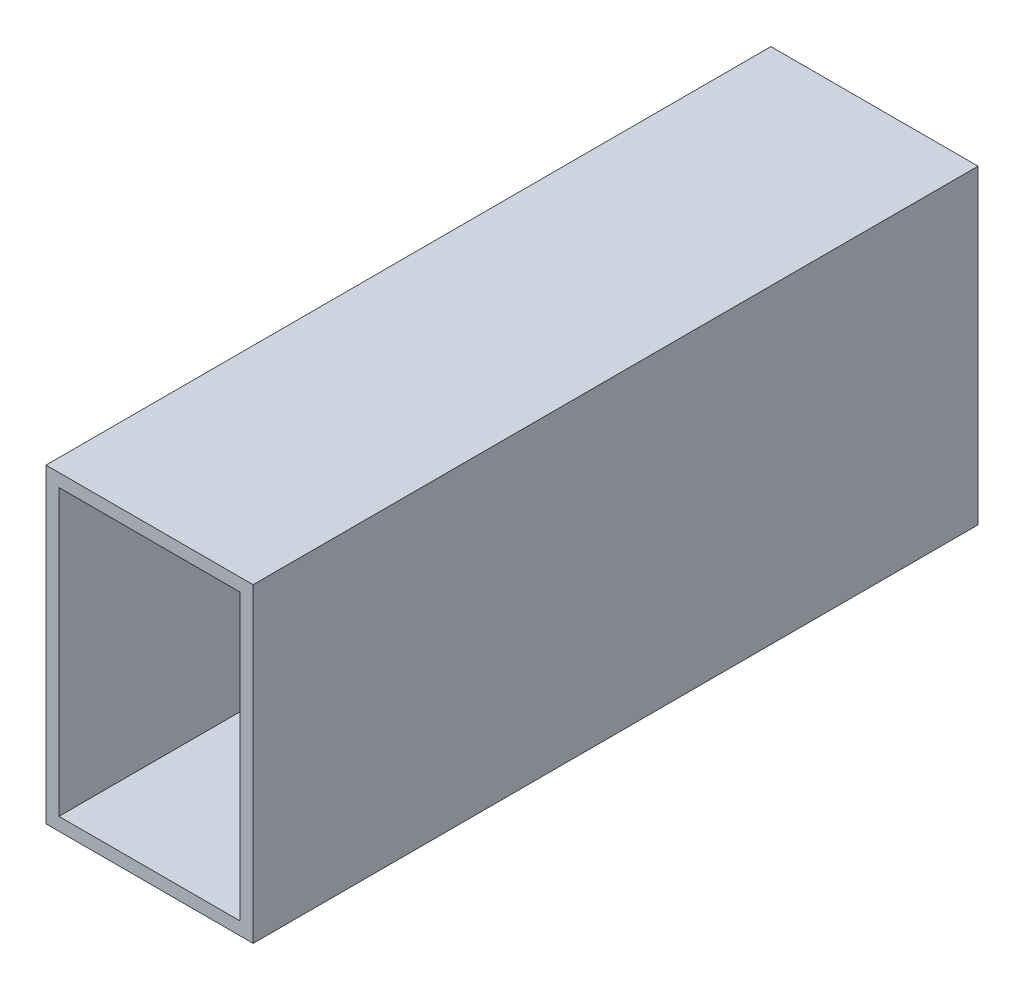
SolidWorks part; units mm, degrees
ref_plane "Front Plane" through (0, 0, 0) normal (0, 0, 1) x (1, 0, 0)
ref_plane "Top Plane" through (0, 0, 0) normal (0, 1, 0) x (1, 0, 0)
ref_plane "Right Plane" through (0, 0, 0) normal (1, 0, 0) x (0, 0, -1)
sketch "Sketch1" plane through (0, 0, 0) normal (0, 0, 1) x (1, 0, 0)
  line L0 (0, 38.1) -> (0, 34.925) construction
  line L1 (-25.4, 38.1) -> (25.4, 38.1)
  line L2 (-25.4, 38.1) -> (-25.4, -38.1)
  line L3 (-25.4, -38.1) -> (25.4, -38.1)
  line L4 (25.4, 38.1) -> (25.4, -38.1)
  line L5 (-25.4, 38.1) -> (25.4, -38.1) construction
  line L6 (-25.4, -38.1) -> (25.4, 38.1) construction
  line L7 (-22.225, 34.925) -> (22.225, 34.925)
  line L8 (-22.225, 34.925) -> (-22.225, -34.925)
  line L9 (-22.225, -34.925) -> (22.225, -34.925)
  line L10 (22.225, 34.925) -> (22.225, -34.925)
  line L11 (22.225, 0) -> (25.4, 0) construction
  line L12 (-22.225, 0) -> (-25.4, 0) construction
  line L13 (0, -34.925) -> (0, -38.1) construction
  point P0 (0, 0)
  dimension "D1" = 76.2
  dimension "D2" = 50.8
  dimension "D3" = 3.175
extrude "Boss-Extrude1" add sketch "Sketch1" along normal blind 177.8
